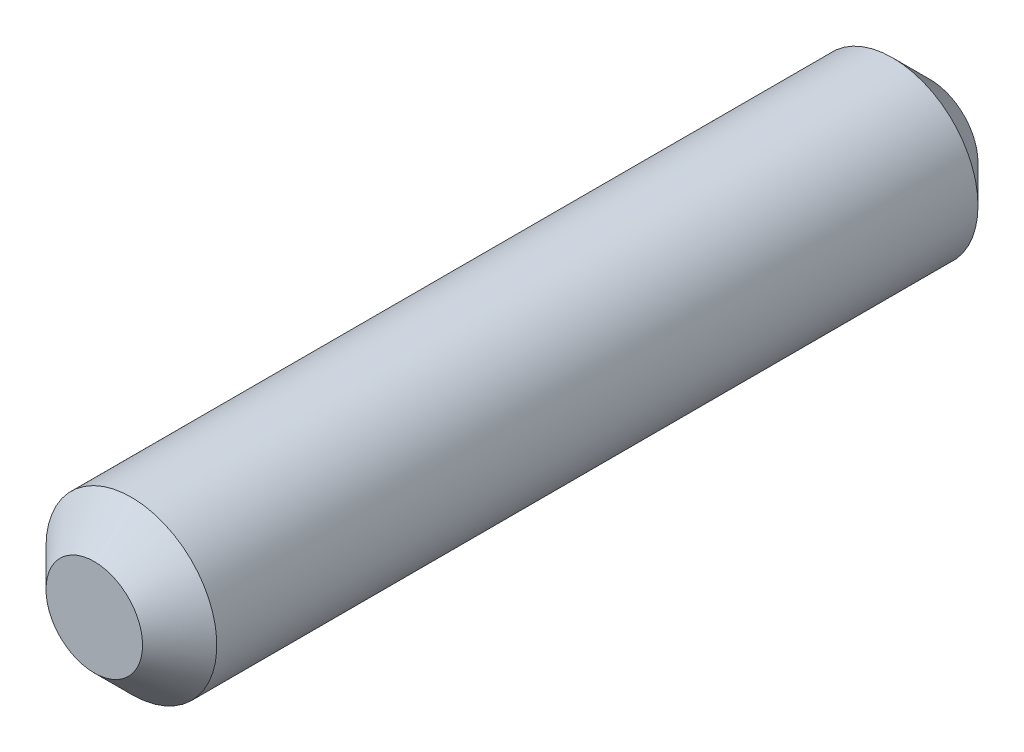
SolidWorks part; units mm, degrees
material "ABS"
ref_plane "Front Plane" through (0, 0, 0) normal (0, 0, 1) x (1, 0, 0)
ref_plane "Top Plane" through (0, 0, 0) normal (0, 1, 0) x (1, 0, 0)
ref_plane "Right Plane" through (0, 0, 0) normal (1, 0, 0) x (0, 0, -1)
sketch "Sketch1" plane through (0, 0, 0) normal (0, 0, 1) x (1, 0, 0)
  circle A0 centre (0, 0) radius 2.3
  dimension "D1" = 4.6
extrude "Boss-Extrude1" add sketch "Sketch1" along normal mid plane 22.5
chamfer "Chamfer1" distance 1 angle 45 2 edges at (2.3, 0, -11.25) (2.3, 0, 11.25)
